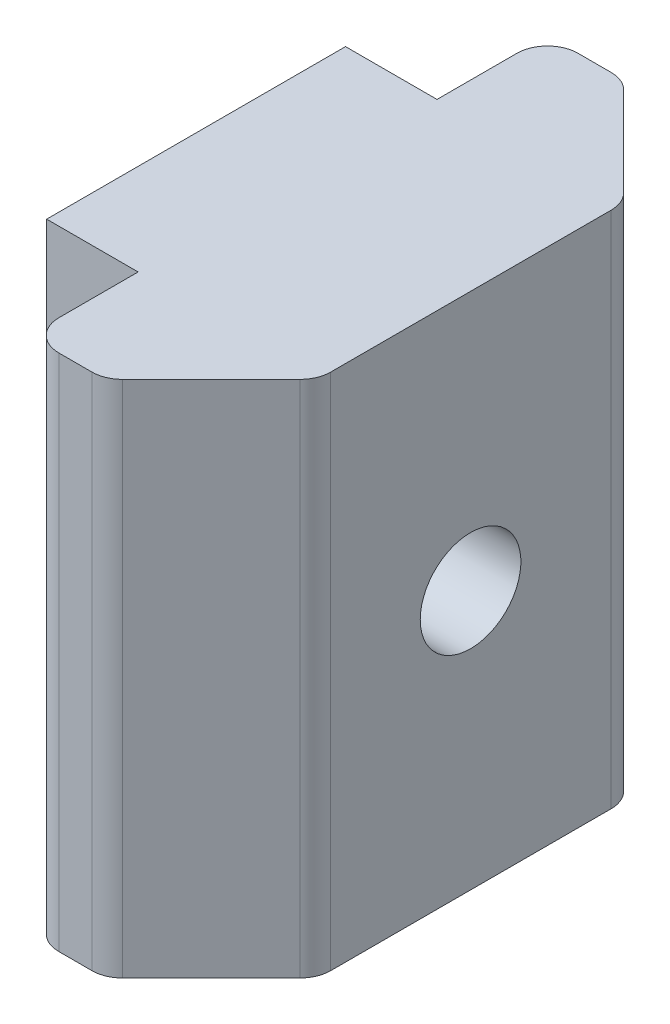
SolidWorks part; units mm, degrees
ref_plane "Front Plane" through (0, 0, 0) normal (0, 0, 1) x (1, 0, 0)
ref_plane "Top Plane" through (0, 0, 0) normal (0, 1, 0) x (1, 0, 0)
ref_plane "Right Plane" through (0, 0, 0) normal (1, 0, 0) x (0, 0, -1)
sketch "Sketch1" plane through (0, 0, 0) normal (0, 1, 0) x (1, 0, 0)
  line L4 (10.2143, -18.2665) -> (13.1285, -15.3523)
  line L5 (9.5072, -18.5594) -> (8.4214, -18.5594)
  line L6 (7.4214, -14.9594) -> (4.4214, -14.9594)
  line L7 (7.4214, -5.1594) -> (4.4214, -5.1594)
  line L8 (4.4214, -14.9594) -> (4.4214, -5.1594)
  line L9 (13.4214, -14.6452) -> (13.4214, -5.4516)
  line L10 (7.4214, -17.5594) -> (7.4214, -14.9594)
  line L11 (10.2143, -1.8303) -> (13.1285, -4.7445)
  line L12 (7.4214, -5.1594) -> (7.4214, -2.5374)
  line L13 (9.5072, -1.5374) -> (8.4214, -1.5374)
  arc A0 (7.4214, -17.5594) -> (8.4214, -18.5594) centre (8.4214, -17.5594) ccw
  arc A1 (9.5072, -18.5594) -> (10.2143, -18.2665) centre (9.5072, -17.5594) ccw
  arc A2 (10.2143, -1.8303) -> (9.5072, -1.5374) centre (9.5072, -2.5374) ccw
  arc A3 (8.4214, -1.5374) -> (7.4214, -2.5374) centre (8.4214, -2.5374) ccw
  arc A4 (13.1285, -15.3523) -> (13.4214, -14.6452) centre (12.4214, -14.6452) ccw
  arc A5 (13.4214, -5.4516) -> (13.1285, -4.7445) centre (12.4214, -5.4516) ccw
extrude "Boss-Extrude1" add sketch "Sketch1" along normal blind 17
sketch "Sketch2" plane through (4.4214, 0, 0) normal (-1, 0, 0) x (0, 0, 1)
  line L0 (10.0594, 17) -> (10.0594, 0) construction
  line L1 (5.1594, 17) -> (14.9594, 17) construction
  line L2 (5.1594, 0) -> (14.9594, 0) construction
  line L3 (5.1594, 8.5) -> (14.9594, 8.5) construction
  line L4 (5.1594, 17) -> (5.1594, 0) construction
  line L5 (14.9594, 17) -> (14.9594, 0) construction
  point P12 (10.0594, 8.5)
hole_wizard "M5 Tapped Hole1" positions "3DSketch1" profile "Sketch3" tap size "M5" standard "ISO"
sketch3d "3DSketch1"
  point P0 (4.4214, 8.5, 10.0594)
sketch "Sketch3" plane through (4.4214, 8.5, 10.0594) normal (0, 1, 0) x (0, 0, 1)
  line L0 (0, 0) -> (0, 9)
  line L1 (0, 9) -> (2.1, 9)
  line L2 (2.1, 9) -> (2.1, 0)
  line L5 (2.1, 0) -> (0, 0)
  line L11 (0, -6.35) -> (0, 107.95) construction
  dimension "Thread Major Dia." = 4.2
  dimension "Thru Tap Drill Depth" = 9
hole_wizard "M4 Tapped Hole1" positions "Sketch5" profile "Sketch4" tap size "M4" standard "ISO" end condition through all
sketch "Sketch5" plane through (4.4214, 0, 0) normal (-1, 0, 0) x (0, 0, 1)
  point P0 (10.0594, 8.5)
sketch "Sketch4" plane through (4.4214, 8.5, 10.0594) normal (0, 1, 0) x (0, 0, 1)
  line L0 (0, 0) -> (0, 9)
  line L1 (0, 9) -> (1.65, 9)
  line L2 (1.65, 9) -> (1.65, 0)
  line L5 (1.65, 0) -> (0, 0)
  line L11 (0, -6.35) -> (0, 107.95) construction
  dimension "Thread Major Dia." = 3.3
  dimension "Thru Tap Drill Depth" = 9
hole_wizard "M6 Tapped Hole1" positions "3DSketch2" profile "Sketch6" tap size "M6" standard "ISO"
sketch3d "3DSketch2"
  point P0 (4.4214, 8.5, 10.0594)
sketch "Sketch6" plane through (4.4214, 8.5, 10.0594) normal (0, 1, 0) x (0, 0, 1)
  line L0 (0, 0) -> (0, 9)
  line L1 (0, 9) -> (2.5, 9)
  line L2 (2.5, 9) -> (2.5, 0)
  line L5 (2.5, 0) -> (0, 0)
  line L11 (0, -6.35) -> (0, 107.95) construction
  dimension "Thread Major Dia." = 5
  dimension "Thru Tap Drill Depth" = 9
hole_wizard "M8 Tapped Hole1" positions "3DSketch3" profile "Sketch7" tap size "M8" standard "ISO"
sketch3d "3DSketch3"
  point P0 (4.4214, 8.5, 10.0594)
sketch "Sketch7" plane through (4.4214, 8.5, 10.0594) normal (0, 1, 0) x (0, 0, 1)
  line L0 (0, 0) -> (0, 9)
  line L1 (0, 9) -> (3.4, 9)
  line L2 (3.4, 9) -> (3.4, 0)
  line L5 (3.4, 0) -> (0, 0)
  line L11 (0, -6.35) -> (0, 107.95) construction
  dimension "Thread Major Dia." = 6.8
  dimension "Thru Tap Drill Depth" = 9
ref_plane "mid-plane" through (0, 0, 10.0594) normal (0, 0, 1) x (1, 0, 0)
